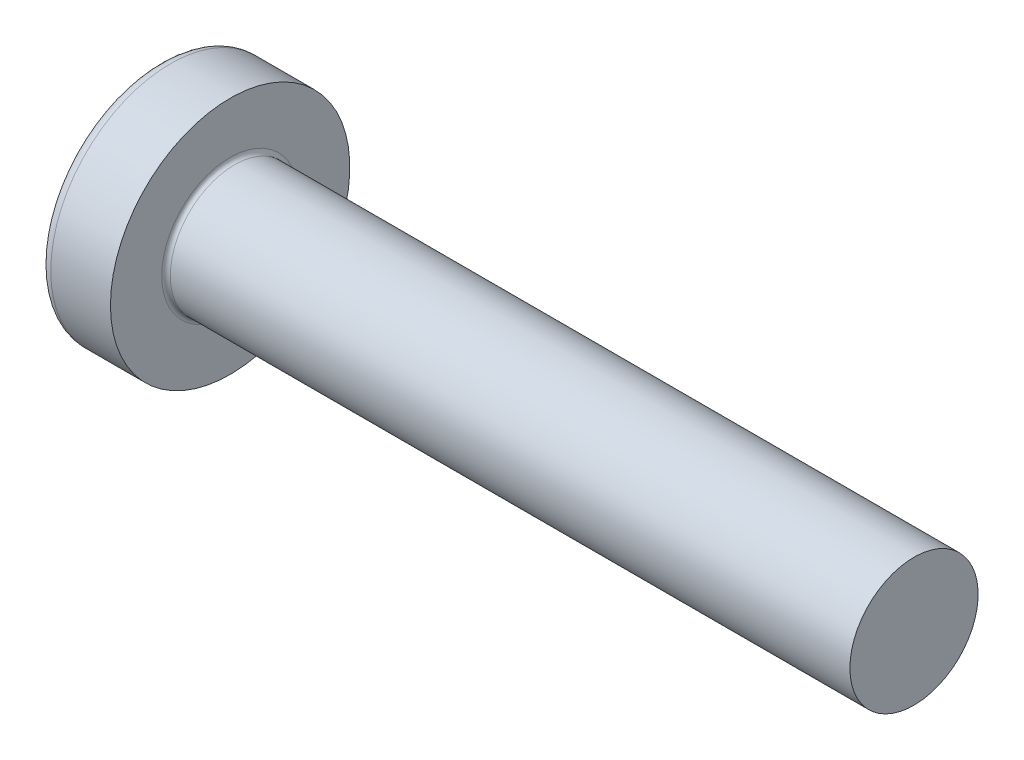
SolidWorks part; units mm, degrees
material "Ductile Iron"
ref_plane "Plane1" through (0, 0, 0) normal (0, 0, 1) x (1, 0, 0)
ref_plane "Plane2" through (0, 0, 0) normal (0, 1, 0) x (1, 0, 0)
ref_plane "Plane3" through (0, 0, 0) normal (1, 0, 0) x (0, 0, -1)
sketch "BodySke" plane through (0, 0, 0) normal (0, 0, 1) x (1, 0, 0)
  line L0 (2.4, 1.5) -> (2.4, 2.8)
  line L1 (2.65, 6.35) -> (2.65, -3.175) construction
  line L2 (-25.4, 0) -> (127, 0) construction
  line L3 (18.4, 0) -> (0, 0)
  line L4 (2.4, 1.5) -> (18.4, 1.5)
  line L5 (18.4, 1.5) -> (18.4, 0)
  line L6 (1.0035, 2.8) -> (2.4, 2.8)
  line L8 (2.4, 6.35) -> (2.4, -3.175) construction
  arc A0 (0.7754, 2.6744) -> (0, 0) centre (5, 0) ccw
  arc A2 (0.7754, 2.6744) -> (1.0035, 2.8) centre (1.0035, 2.53) cw
  dimension "Head_fillet_rad" = 0.27
  dimension "Head_crown_rad" = 5
  dimension "Head_ht" = 2.4
  dimension "Diameter" = 3
  dimension "Length" = 16
  dimension "Head_dia" = 5.6
  dimension "Advance" = 0.5
  dimension "Thread_nom" = 16
revolve "Base-Revolve" add sketch "BodySke"
cosmetic thread "ThreadCosmetic" [suppressed]
fillet "Fillet1" radius 0.1 1 edges at (2.4, 0, 1.5)
sketch "Sketch3" plane through (0, 0, 0) normal (1, 0, 0) x (0, 0, -1)
  line L0 (0.37, -1.4) -> (-0.37, -1.4)
  line L1 (0.37, -1.4) -> (0.37, 1.4)
  line L2 (-0.37, 1.4) -> (0.37, 1.4)
  line L3 (-0.37, 1.4) -> (-0.37, -1.4)
  dimension "D1" = 1.4
  dimension "Cross_dia" = 2.8
  dimension "D2" = 0.37
  dimension "Cross_width" = 0.74
ref_plane "Plane4" through (1.75, 0, 0) normal (1, 0, 0) x (0, 0, -1)
sketch "Sketch4" plane through (1.75, 0, 0) normal (1, 0, 0) x (0, 0, -1)
  line L0 (0.37, -0.5275) -> (-0.37, -0.5275)
  line L1 (0.37, -0.5275) -> (0.37, 0.5275)
  line L2 (-0.37, 0.5275) -> (0.37, 0.5275)
  line L3 (-0.37, 0.5275) -> (-0.37, -0.5275)
  dimension "D1" = 0.74
  dimension "D2" = 1.055
  dimension "D3" = 0.37
  dimension "D4" = 0.5275
loft "Recess" cut profiles "Sketch3", "Sketch4"
pattern_circular "RecPat" count 2 every 90 about axis through (0, 0, 0) along (1, 0, 0) of "Recess"
sketch "RecCorSke" plane through (0, 0, 0) normal (0, 0, 1) x (1, 0, 0)
  line L0 (-3.175, 0) -> (15.875, 0) construction
  line L1 (-25.4, 0) -> (127, 0) construction
  line L2 (0, 0) -> (0, 0.6784)
  line L3 (0, 0.6784) -> (1.75, 0.556)
  line L4 (1.75, 0.556) -> (1.9307, 0)
  line L5 (1.9307, 0) -> (0, 0)
  dimension "Diameter" = 1.112
  dimension "Depth" = 1.75
  dimension "Draft_angle" = 4
  dimension "Bottom_angle" = 18
revolve "RecessCore" cut sketch "RecCorSke" angle 360 about L0
sketch "ThdSchSke" plane through (0, 0, 0) normal (0, 0, 1) x (1, 0, 0)
  line L0 (3.4, -1.2195) -> (3.2036, -1.5)
  line L1 (3.4, -1.2195) -> (3.5964, -1.5)
  line L2 (3.5964, -1.5) -> (3.5964, -1.875)
  line L3 (-3.175, 0) -> (5.1513, 0) construction
  line L5 (3.5964, -1.875) -> (3.2036, -1.875)
  line L6 (3.2036, -1.875) -> (3.2036, -1.5)
  dimension "Thread_minor" = 2.439
  dimension "Diameter" = 3
  dimension "Start" = 3.4
  dimension "SideAngle" = 55
  dimension "VeeAngle" = 70
  dimension "Overcut" = 3.75
revolve "ThreadSchematic" [suppressed] cut sketch "ThdSchSke" angle 360 about L3
pattern_linear "ThdSchPat" [suppressed]
equation "\"D1@Sketch3\" = \"Cross_dia@Sketch3\" / 2"
equation "\"D2@Sketch3\" = \"Cross_width@Sketch3\" / 2"
equation "\"Depth@RecCorSke\" = \"Cross_depth@Plane4\""
equation "\"D1@Sketch4\" = \"Cross_width@Sketch3\""
equation "\"D2@Sketch4\" = \"Cross_dia@Sketch3\" - 2.0 * \"Cross_depth@Plane4\" * tan(26.5  * 0.017453292)"
equation "\"D3@Sketch4\" = \"D1@Sketch4\" / 2"
equation "\"D4@Sketch4\" = \"D2@Sketch4\" / 2"
equation "\"Thread_length@ThreadCosmetic\" = ((sgn( (\"Length@BodySke\" - \"Advance@BodySke\" * 2.0 ) - \"Thread_nom@BodySke\" )-1)*( (\"Length@BodySke\" - \"Advance@BodySke\" * 2.0 ) - \"Thread_nom@BodySke\" ))/-2+ \"Thread_nom@BodySke\""
equation "\"Thread_minor@ThdSchSke\" = \"Thread_minor@ThreadCosmetic\""
equation "\"Diameter@ThdSchSke\" = \"Diameter@BodySke\""
equation "\"Overcut@ThdSchSke\" = \"Diameter@BodySke\" * 1.25"
equation "\"Start@ThdSchSke\" = \"Head_ht@BodySke\" + \"Length@BodySke\" - \"Thread_length@ThreadCosmetic\"  '---Non-countersunk---"
equation "\"Num_threads@ThdSchPat\" = int( \"Thread_length@ThreadCosmetic\" / \"Advance@BodySke\" + 0.999 )  + 1"
equation "\"Advance@ThdSchPat\" = \"Thread_length@ThreadCosmetic\" /  (\"Num_threads@ThdSchPat\" - 1) 'relax it"
